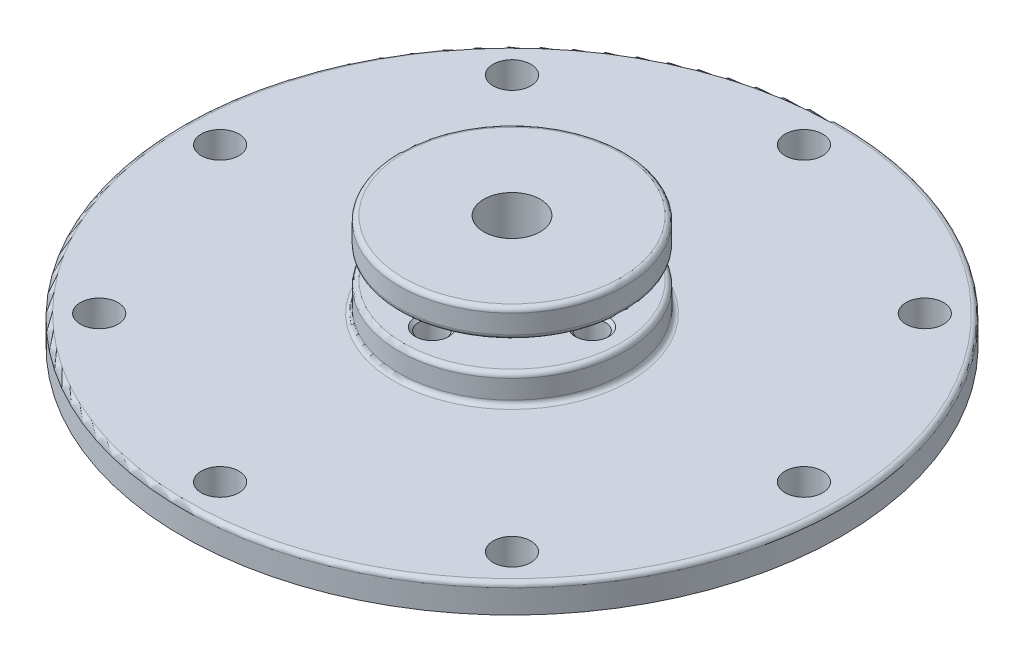
SolidWorks part; units mm, degrees
ref_plane "Front Plane" through (0, 0, 0) normal (0, 0, 1) x (1, 0, 0)
ref_plane "Top Plane" through (0, 0, 0) normal (0, 1, 0) x (1, 0, 0)
ref_plane "Right Plane" through (0, 0, 0) normal (1, 0, 0) x (0, 0, -1)
sketch "Sketch1" plane through (0, 0, 0) normal (0, 0, 1) x (1, 0, 0)
  line L0 (0, 16.3067) -> (0, -16.4684) construction
  line L2 (-4.5, 0) -> (-4.5, 4)
  line L3 (-4.5, 4) -> (-6, 4)
  line L4 (-6, 4) -> (-6, 10)
  line L5 (-6, 10) -> (-11.5, 10)
  line L6 (-12, 9.5) -> (-12, 7.5)
  line L7 (-12.5, 7) -> (-34.5, 7)
  line L8 (-35, 6.5) -> (-35, 4)
  line L9 (-35, 4) -> (-22.5, 4)
  line L10 (-22.5, 4) -> (-22.5, 0)
  line L11 (-22.5, 0) -> (-4.5, 0)
  arc A0 (-34.5, 7) -> (-35, 6.5) centre (-34.5, 6.5) ccw
  arc A1 (-12, 7.5) -> (-12.5, 7) centre (-12.5, 7.5) cw
  arc A2 (-11.5, 10) -> (-12, 9.5) centre (-11.5, 9.5) ccw
  point P15 (-35, 7)
  point P18 (-12, 7)
  point P21 (-12, 10)
  dimension "D10" = 0.5
  dimension "D1" = 9
  dimension "D2" = 12
  dimension "D3" = 24
  dimension "D4" = 6
  dimension "D5" = 3
  dimension "D6" = 4
  dimension "D7" = 3
  dimension "D8" = 45
  dimension "D9" = 70
revolve "Revolve1" add sketch "Sketch1" angle 360 about L0
sketch "Sketch2" plane through (0, 10, 0) normal (0, 1, 0) x (1, 0, 0)
  circle A0 centre (0, 0) radius 8.5 construction
  circle A1 centre (0, 0) radius 31 construction
  circle A2 centre (0, 0) radius 12 construction
  circle A4 centre (0, 31) radius 2
  circle A5 centre (21.9203, 21.9203) radius 2
  circle A6 centre (31, 0) radius 2
  circle A7 centre (21.9203, -21.9203) radius 2
  circle A8 centre (0, -31) radius 2
  circle A9 centre (-21.9203, -21.9203) radius 2
  circle A10 centre (-31, 0) radius 2
  circle A11 centre (-21.9203, 21.9203) radius 2
  point P4 (0, 8.5)
  point P5 (-8.5, 0)
  point P8 (0, -8.5)
  point P9 (8.5, 0)
  point P31 (0, 0)
  dimension "D1" = 17
  dimension "D2" = 62
  dimension "D3" = 4
  dimension "D5" = 21.9203
  dimension "D4" = 8
extrude "Cut-Extrude1" cut sketch "Sketch2" against normal blind 10
sketch "Sketch5" plane through (0, 10, 0) normal (0, 1, 0) x (1, 0, 0)
  point P0 (0, 8.5)
  point P3 (-8.5, 0)
  point P6 (8.5, 0)
  point P9 (0, -8.5)
hole_wizard "M3.5x0.6 Tapped Hole1" positions "Sketch5" profile "Sketch7" tap size "M3.5x0.6" standard "ANSI Metric"
cosmetic thread "Hole Thread1" parameters "D1"=7, "D2"=3.5
cosmetic thread "Hole Thread2" parameters "D1"=7, "D2"=3.5
cosmetic thread "Hole Thread3" parameters "D1"=7, "D2"=3.5
cosmetic thread "Hole Thread4" parameters "D1"=7, "D2"=3.5
sketch "Sketch7" plane through (0, 10, -8.5) normal (1, 0, 0) x (0, 0, 1)
  line L0 (0, 0) -> (0, 8)
  line L1 (0, 8) -> (1.45, 7.1288)
  line L2 (1.45, 7.1288) -> (1.45, 0.325)
  line L3 (1.45, 0.325) -> (1.775, 0)
  line L5 (1.775, 0) -> (0, 0)
  line L6 (-1.45, 0.325) -> (-1.775, 0) construction
  line L10 (0, 8) -> (-1.45, 7.1288) construction
  line L11 (0, -6.35) -> (0, 107.95) construction
  dimension "Tap Drill Dia." = 2.9
  dimension "Tap Drill Depth" = 8
  dimension "Near C'Sink Dia." = 3.55
  dimension "Near C'Sink Angle" = 90
  dimension "Drill Angle" = 118
sketch "Sketch9" plane through (0, 0, 0) normal (0, 0, 1) x (1, 0, 0)
  line L0 (-3, 0) -> (-4.5, 0)
  line L1 (-4.5, 0) -> (4.5, 0) construction
  line L2 (-22.5, 0) -> (22.5, 0) construction
  line L3 (-4.5, 0) -> (-4.5, 4)
  line L4 (6, 4) -> (-6, 4) construction
  line L5 (4.5, 4) -> (-4.5, 4) construction
  line L6 (-4.5, 4) -> (-6, 4)
  line L7 (-22.5, 4) -> (22.5, 4) construction
  line L8 (-6, 4) -> (-6, 6)
  line L11 (-6, 6) -> (-3, 6)
  line L12 (-3, 6) -> (-3, 0)
  line L13 (0, 11.6459) -> (0, -0.9412) construction
  dimension "D1" = 3
  dimension "D2" = 3
  dimension "D3" = 1.5
  dimension "D4" = 2
revolve "Revolve2" add sketch "Sketch9" angle 360 about L13
sketch "Sketch11" plane through (0, 0, 0) normal (0, 0, 1) x (1, 0, 0)
  line L4 (-3, 9) -> (-3, 6)
  line L6 (3, 6) -> (-3, 6) construction
  line L7 (6, 6) -> (-6, 6) construction
  line L8 (-3, 9) -> (-6, 9)
  line L10 (-6, 9) -> (-6, 6)
  line L11 (-6, 6) -> (-3, 6)
  dimension "D1" = 3
  dimension "D2" = 3
  dimension "D3" = 3
  dimension "D4" = 3
revolve "Revolve3" add sketch "Sketch11" angle 360 about axis through (0, 11.6459, 0) along (0, 1, 0)
sketch "Sketch12" plane through (0, 0, 0) normal (0, 0, 1) x (1, 0, 0)
  line L1 (0, 4) -> (0, 10) construction
  line L2 (-6, 13) -> (-11.5, 13)
  line L3 (-12, 13.5) -> (-12, 15.5)
  line L4 (-11.5, 16) -> (-3, 16)
  line L6 (-6, 9) -> (-6, 13)
  line L8 (-3, 9) -> (-6, 9)
  line L9 (-3, 16) -> (-3, 9)
  arc A0 (-11.5, 13) -> (-12, 13.5) centre (-11.5, 13.5) cw
  arc A1 (-12, 15.5) -> (-11.5, 16) centre (-11.5, 15.5) cw
  point P10 (-12, 13)
  point P13 (-12, 16)
  dimension "D7" = 0.5
  dimension "D1" = 3
  dimension "D2" = 6
  dimension "D3" = 12
  dimension "D4" = 4
  dimension "D5" = 3
  dimension "D6" = 9
revolve "Revolve4" add sketch "Sketch12" angle 360 about axis through (0, 11.6459, 0) along (0, 1, 0)
